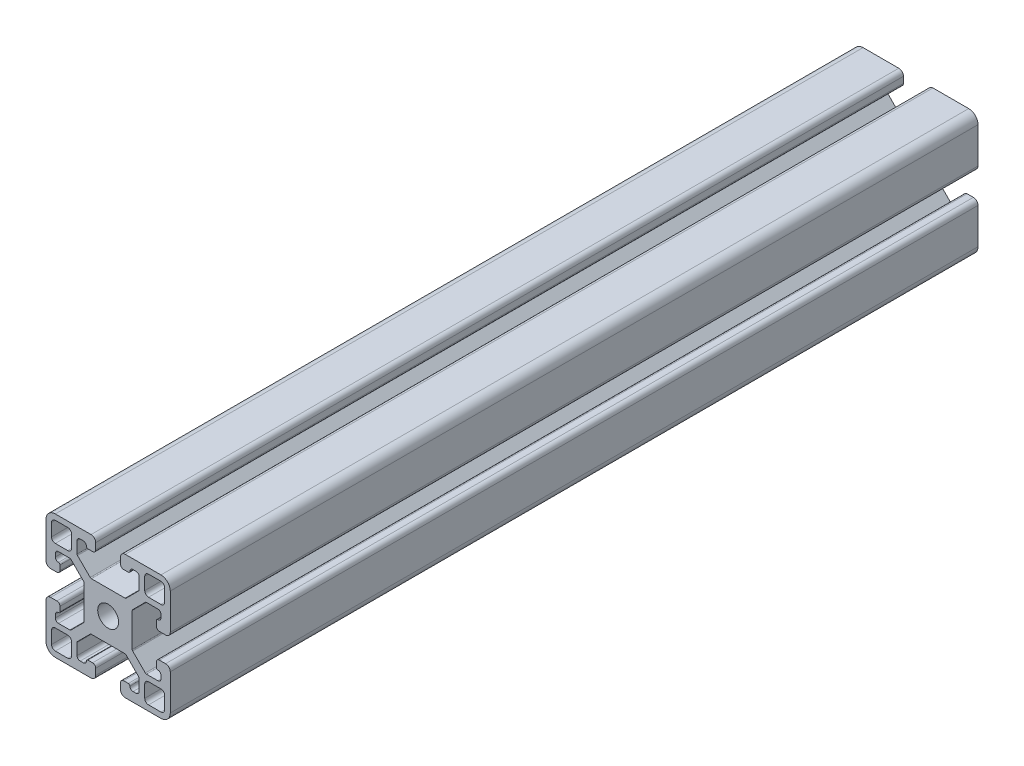
SolidWorks part; units mm, degrees
ref_plane "Front Plane" through (0, 0, 0) normal (0, 0, 1) x (1, 0, 0)
ref_plane "Top Plane" through (0, 0, 0) normal (0, 1, 0) x (1, 0, 0)
ref_plane "Right Plane" through (0, 0, 0) normal (1, 0, 0) x (0, 0, -1)
sketch "Sketch1" plane through (0, 0, 0) normal (0, 0, 1) x (1, 0, 0)
  line B0 (-17, 11.78) -> (-13, 11.78)
  arc B1 (-13, 11.78) -> (-11.78, 13) centre (-13, 13) ccw
  line B2 (-11.78, 13) -> (-11.78, 17)
  arc B3 (-11.78, 17) -> (-13, 18.22) centre (-13, 17) ccw
  line B4 (-13, 18.22) -> (-17, 18.22)
  arc B5 (-17, 18.22) -> (-18.22, 17) centre (-17, 17) ccw
  line B6 (-18.22, 17) -> (-18.22, 13)
  arc B7 (-18.22, 13) -> (-17, 11.78) centre (-17, 13) ccw
  line B8 (-18.22, -13) -> (-18.22, -17)
  arc B9 (-18.22, -17) -> (-17, -18.22) centre (-17, -17) ccw
  line B10 (-17, -18.22) -> (-13, -18.22)
  arc B11 (-13, -18.22) -> (-11.78, -17) centre (-13, -17) ccw
  line B12 (-11.78, -17) -> (-11.78, -13)
  arc B13 (-11.78, -13) -> (-13, -11.78) centre (-13, -13) ccw
  line B14 (-13, -11.78) -> (-17, -11.78)
  arc B15 (-17, -11.78) -> (-18.22, -13) centre (-17, -13) ccw
  line B16 (13, -18.22) -> (17, -18.22)
  arc B17 (17, -18.22) -> (18.22, -17) centre (17, -17) ccw
  line B18 (18.22, -17) -> (18.22, -13)
  arc B19 (18.22, -13) -> (17, -11.78) centre (17, -13) ccw
  line B20 (17, -11.78) -> (13, -11.78)
  arc B21 (13, -11.78) -> (11.78, -13) centre (13, -13) ccw
  line B22 (11.78, -13) -> (11.78, -17)
  arc B23 (11.78, -17) -> (13, -18.22) centre (13, -17) ccw
  line B24 (18.22, 13) -> (18.22, 17)
  arc B25 (18.22, 17) -> (17, 18.22) centre (17, 17) ccw
  line B26 (17, 18.22) -> (13, 18.22)
  arc B27 (13, 18.22) -> (11.78, 17) centre (13, 17) ccw
  line B28 (11.78, 17) -> (11.78, 13)
  arc B29 (11.78, 13) -> (13, 11.78) centre (13, 13) ccw
  line B30 (13, 11.78) -> (17, 11.78)
  arc B31 (17, 11.78) -> (18.22, 13) centre (17, 13) ccw
  line B32 (-9.8536, -11.9786) -> (-5.7714, -7.8964)
  arc B33 (-5.4179, -7.75) -> (-5.7714, -7.8964) centre (-5.4179, -8.25) ccw
  line B34 (-5.4179, -7.75) -> (5.4179, -7.75)
  arc B35 (5.7714, -7.8964) -> (5.4179, -7.75) centre (5.4179, -8.25) ccw
  line B36 (5.7714, -7.8964) -> (9.8536, -11.9786)
  arc B37 (10, -12.3321) -> (9.8536, -11.9786) centre (9.5, -12.3321) ccw
  line B38 (10, -12.3321) -> (10, -16)
  arc B39 (9, -17) -> (10, -16) centre (9, -16) ccw
  line B40 (9, -17) -> (8, -17)
  arc B41 (7, -16) -> (8, -17) centre (8, -16) ccw
  arc B42 (7, -16) -> (6.5, -15.5) centre (6.5, -16) ccw
  line B43 (6.5, -15.5) -> (5, -15.5)
  arc B44 (5, -15.5) -> (4, -16.5) centre (5, -16.5) ccw
  line B45 (4, -16.5) -> (4, -18.5)
  arc B46 (4, -18.5) -> (5.5, -20) centre (5.5, -18.5) ccw
  line B47 (5.5, -20) -> (17, -20)
  arc B48 (17, -20) -> (20, -17) centre (17, -17) ccw
  line B49 (20, -17) -> (20, -5.5)
  arc B50 (20, -5.5) -> (18.5, -4) centre (18.5, -5.5) ccw
  line B51 (18.5, -4) -> (16.5, -4)
  arc B52 (16.5, -4) -> (15.5, -5) centre (16.5, -5) ccw
  line B53 (15.5, -5) -> (15.5, -6.5)
  arc B54 (15.5, -6.5) -> (16, -7) centre (16, -6.5) ccw
  arc B55 (17, -8) -> (16, -7) centre (16, -8) ccw
  line B56 (17, -8) -> (17, -9)
  arc B57 (16, -10) -> (17, -9) centre (16, -9) ccw
  line B58 (16, -10) -> (12.3321, -10)
  arc B59 (11.9786, -9.8536) -> (12.3321, -10) centre (12.3321, -9.5) ccw
  line B60 (11.9786, -9.8536) -> (7.8964, -5.7714)
  arc B61 (7.75, -5.4179) -> (7.8964, -5.7714) centre (8.25, -5.4179) ccw
  line B62 (7.75, -5.4179) -> (7.75, 5.4179)
  arc B63 (7.8964, 5.7714) -> (7.75, 5.4179) centre (8.25, 5.4179) ccw
  line B64 (7.8964, 5.7714) -> (11.9786, 9.8536)
  arc B65 (12.3321, 10) -> (11.9786, 9.8536) centre (12.3321, 9.5) ccw
  line B66 (12.3321, 10) -> (16, 10)
  arc B67 (17, 9) -> (16, 10) centre (16, 9) ccw
  line B68 (17, 9) -> (17, 8)
  arc B69 (16, 7) -> (17, 8) centre (16, 8) ccw
  arc B70 (16, 7) -> (15.5, 6.5) centre (16, 6.5) ccw
  line B71 (15.5, 6.5) -> (15.5, 5)
  arc B72 (15.5, 5) -> (16.5, 4) centre (16.5, 5) ccw
  line B73 (16.5, 4) -> (18.5, 4)
  arc B74 (18.5, 4) -> (20, 5.5) centre (18.5, 5.5) ccw
  line B75 (20, 5.5) -> (20, 17)
  arc B76 (20, 17) -> (17, 20) centre (17, 17) ccw
  line B77 (17, 20) -> (5.5, 20)
  arc B78 (5.5, 20) -> (4, 18.5) centre (5.5, 18.5) ccw
  line B79 (4, 18.5) -> (4, 16.5)
  arc B80 (4, 16.5) -> (5, 15.5) centre (5, 16.5) ccw
  line B81 (5, 15.5) -> (6.5, 15.5)
  arc B82 (6.5, 15.5) -> (7, 16) centre (6.5, 16) ccw
  arc B83 (8, 17) -> (7, 16) centre (8, 16) ccw
  line B84 (8, 17) -> (9, 17)
  arc B85 (10, 16) -> (9, 17) centre (9, 16) ccw
  line B86 (10, 16) -> (10, 12.3321)
  arc B87 (9.8536, 11.9786) -> (10, 12.3321) centre (9.5, 12.3321) ccw
  line B88 (9.8536, 11.9786) -> (5.7714, 7.8964)
  arc B89 (5.4179, 7.75) -> (5.7714, 7.8964) centre (5.4179, 8.25) ccw
  line B90 (5.4179, 7.75) -> (-5.4179, 7.75)
  arc B91 (-5.7714, 7.8964) -> (-5.4179, 7.75) centre (-5.4179, 8.25) ccw
  line B92 (-5.7714, 7.8964) -> (-9.8536, 11.9786)
  arc B93 (-10, 12.3321) -> (-9.8536, 11.9786) centre (-9.5, 12.3321) ccw
  line B94 (-10, 12.3321) -> (-10, 16)
  arc B95 (-9, 17) -> (-10, 16) centre (-9, 16) ccw
  line B96 (-9, 17) -> (-8, 17)
  arc B97 (-7, 16) -> (-8, 17) centre (-8, 16) ccw
  arc B98 (-7, 16) -> (-6.5, 15.5) centre (-6.5, 16) ccw
  line B99 (-6.5, 15.5) -> (-5, 15.5)
  arc B100 (-5, 15.5) -> (-4, 16.5) centre (-5, 16.5) ccw
  line B101 (-4, 16.5) -> (-4, 18.5)
  arc B102 (-4, 18.5) -> (-5.5, 20) centre (-5.5, 18.5) ccw
  line B103 (-5.5, 20) -> (-17, 20)
  arc B104 (-17, 20) -> (-20, 17) centre (-17, 17) ccw
  line B105 (-20, 17) -> (-20, 5.5)
  arc B106 (-20, 5.5) -> (-18.5, 4) centre (-18.5, 5.5) ccw
  line B107 (-18.5, 4) -> (-16.5, 4)
  arc B108 (-16.5, 4) -> (-15.5, 5) centre (-16.5, 5) ccw
  line B109 (-15.5, 5) -> (-15.5, 6.5)
  arc B110 (-15.5, 6.5) -> (-16, 7) centre (-16, 6.5) ccw
  arc B111 (-17, 8) -> (-16, 7) centre (-16, 8) ccw
  line B112 (-17, 8) -> (-17, 9)
  arc B113 (-16, 10) -> (-17, 9) centre (-16, 9) ccw
  line B114 (-16, 10) -> (-12.3321, 10)
  arc B115 (-11.9786, 9.8536) -> (-12.3321, 10) centre (-12.3321, 9.5) ccw
  line B116 (-11.9786, 9.8536) -> (-7.8964, 5.7714)
  arc B117 (-7.75, 5.4179) -> (-7.8964, 5.7714) centre (-8.25, 5.4179) ccw
  line B118 (-7.75, 5.4179) -> (-7.75, -5.4179)
  arc B119 (-7.8964, -5.7714) -> (-7.75, -5.4179) centre (-8.25, -5.4179) ccw
  line B120 (-7.8964, -5.7714) -> (-11.9786, -9.8536)
  arc B121 (-12.3321, -10) -> (-11.9786, -9.8536) centre (-12.3321, -9.5) ccw
  line B122 (-12.3321, -10) -> (-16, -10)
  arc B123 (-17, -9) -> (-16, -10) centre (-16, -9) ccw
  line B124 (-17, -9) -> (-17, -8)
  arc B125 (-16, -7) -> (-17, -8) centre (-16, -8) ccw
  arc B126 (-16, -7) -> (-15.5, -6.5) centre (-16, -6.5) ccw
  line B127 (-15.5, -6.5) -> (-15.5, -5)
  arc B128 (-15.5, -5) -> (-16.5, -4) centre (-16.5, -5) ccw
  line B129 (-16.5, -4) -> (-18.5, -4)
  arc B130 (-18.5, -4) -> (-20, -5.5) centre (-18.5, -5.5) ccw
  line B131 (-20, -5.5) -> (-20, -17)
  arc B132 (-20, -17) -> (-17, -20) centre (-17, -17) ccw
  line B133 (-17, -20) -> (-5.5, -20)
  arc B134 (-5.5, -20) -> (-4, -18.5) centre (-5.5, -18.5) ccw
  line B135 (-4, -18.5) -> (-4, -16.5)
  arc B136 (-4, -16.5) -> (-5, -15.5) centre (-5, -16.5) ccw
  line B137 (-5, -15.5) -> (-6.5, -15.5)
  arc B138 (-6.5, -15.5) -> (-7, -16) centre (-6.5, -16) ccw
  arc B139 (-8, -17) -> (-7, -16) centre (-8, -16) ccw
  line B140 (-8, -17) -> (-9, -17)
  arc B141 (-10, -16) -> (-9, -17) centre (-9, -16) ccw
  line B142 (-10, -16) -> (-10, -12.3321)
  arc B143 (-9.8536, -11.9786) -> (-10, -12.3321) centre (-9.5, -12.3321) ccw
  circle B144 centre (0, 0) radius 3.35
sketch_block_instance "S8-4040 - S-1"
sketch_block "S8-4040 - S"
extrude "Boss-Extrude1" add sketch "Sketch1" along normal blind 260
